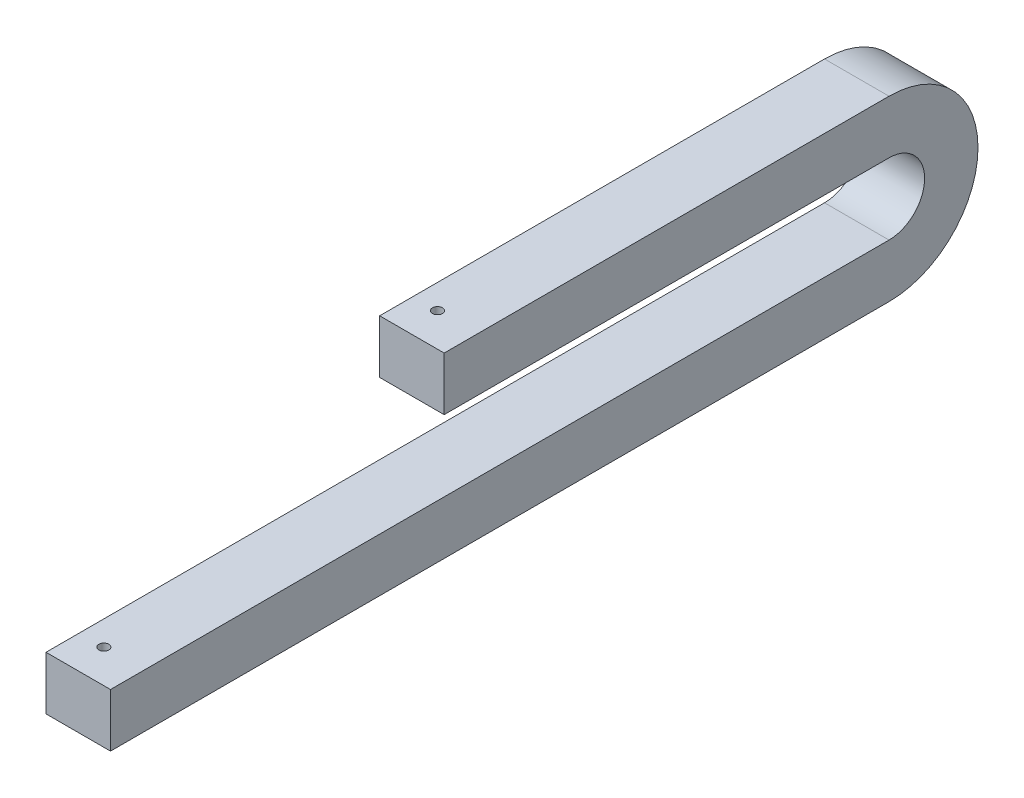
SolidWorks part; units mm, degrees
ref_plane "前视基准面" through (0, 0, 0) normal (0, 0, 1) x (1, 0, 0)
ref_plane "上视基准面" through (0, 0, 0) normal (0, 1, 0) x (1, 0, 0)
ref_plane "右视基准面" through (0, 0, 0) normal (1, 0, 0) x (0, 0, -1)
sketch "草图1" plane through (0, 0, 0) normal (1, 0, 0) x (0, 0, -1)
  line L0 (0, 0) -> (350, 0)
  line L1 (0, 0) -> (0, -24)
  line L2 (0, -24) -> (350, -24)
  line L3 (150, 56) -> (150, 32)
  line L4 (350, 32) -> (150, 32)
  line L5 (350, 56) -> (150, 56)
  arc A0 (350, 0) -> (350, 32) centre (350, 16) ccw
  arc A1 (350, -24) -> (350, 56) centre (350, 16) ccw
  dimension "D1" = 24
  dimension "D2" = 350
  dimension "D3" = 350
  dimension "D4" = 80
  dimension "D5" = 200
  dimension "D6" = 24
extrude "凸台-拉伸1" add sketch "草图1" along normal blind 29
sketch "草图2" plane through (0, 0, 0) normal (0, 1, 0) x (1, 0, 0)
  line L0 (0, 350) -> (0, 0) construction
  line L1 (29, 0) -> (0, 0) construction
  circle A0 centre (36, 15) radius 2.25
  circle A1 centre (11, 15) radius 2.25
  dimension "D1" = 25
  dimension "D2" = 4.5
  dimension "D3" = 4.5
  dimension "D4" = 11
  dimension "D5" = 15
  dimension "D6" = 15
extrude "切除-拉伸1" cut sketch "草图2" against normal blind 90
sketch "草图3" plane through (0, 56, 0) normal (0, 1, 0) x (1, 0, 0)
  line L0 (0, 350) -> (0, 150) construction
  line L1 (29, 150) -> (0, 150) construction
  circle A0 centre (11, 165) radius 2.25
  circle A1 centre (36, 165) radius 2.25
  dimension "D1" = 4.5
  dimension "D2" = 4.5
  dimension "D3" = 25
  dimension "D4" = 11
  dimension "D6" = 15
  dimension "D5" = 15
extrude "切除-拉伸2" cut sketch "草图3" against normal blind 40
